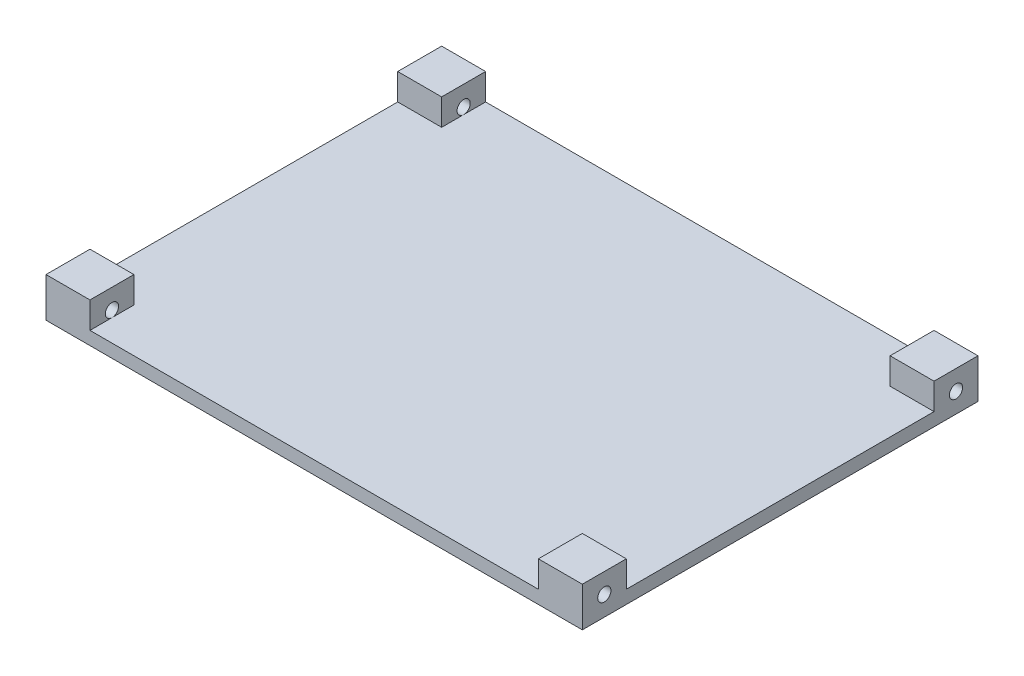
SolidWorks part; units mm, degrees
ref_plane "Front Plane" through (0, 0, 0) normal (0, 0, 1) x (1, 0, 0)
ref_plane "Top Plane" through (0, 0, 0) normal (0, 1, 0) x (1, 0, 0)
ref_plane "Right Plane" through (0, 0, 0) normal (1, 0, 0) x (0, 0, -1)
sketch "Sketch1" plane through (0, 0, 0) normal (0, 1, 0) x (1, 0, 0)
  line L1 (0, 0) -> (122, 0)
  line L2 (0, 0) -> (0, 90)
  line L3 (0, 90) -> (122, 90)
  line L4 (122, 0) -> (122, 90)
  dimension "D1" = 122
  dimension "D2" = 90
extrude "Boss-Extrude1" add sketch "Sketch1" along normal blind 3
sketch "Sketch2" plane through (0, 3, 0) normal (0, 1, 0) x (1, 0, 0)
  line L1 (0, 0) -> (10, 0)
  line L2 (0, 0) -> (0, 10)
  line L3 (0, 10) -> (7.7811, 10)
  line L4 (10, 0) -> (10, 5.7066)
  line L5 (0, 90) -> (10, 90)
  line L6 (0, 90) -> (0, 80)
  line L7 (0, 80) -> (10, 80)
  line L8 (10, 90) -> (10, 80)
  line L9 (122, 90) -> (112, 90)
  line L10 (122, 90) -> (122, 80)
  line L11 (122, 80) -> (112, 80)
  line L12 (112, 90) -> (112, 80)
  line L13 (122, 0) -> (112, 0)
  line L14 (122, 0) -> (122, 10)
  line L15 (122, 10) -> (112, 10)
  line L16 (112, 0) -> (112, 10)
  line L17 (7.7811, 10) -> (10, 10)
  line L19 (10, 10) -> (10, 5.7066)
  dimension "D10" = 10
  dimension "D11" = 10
  dimension "D12" = 10
  dimension "D13" = 10
  dimension "D14" = 10
  dimension "D15" = 10
extrude "Boss-Extrude2" add sketch "Sketch2" along normal blind 6
sketch "Sketch4" plane through (0, 0, 0) normal (-1, 0, 0) x (0, 0, 1)
  circle A0 centre (-85, 4.5) radius 1.5
  circle A1 centre (-5, 4.5) radius 1.5
  dimension "D1" = 3
  dimension "D2" = 3
extrude "Cut-Extrude2" cut sketch "Sketch4" against normal up to next
sketch "Sketch5" plane through (122, 0, 0) normal (1, 0, 0) x (0, 0, -1)
  circle A0 centre (85, 4.5) radius 1.5
  circle A1 centre (5, 4.5) radius 1.5
extrude "Cut-Extrude3" cut sketch "Sketch5" against normal up to next
